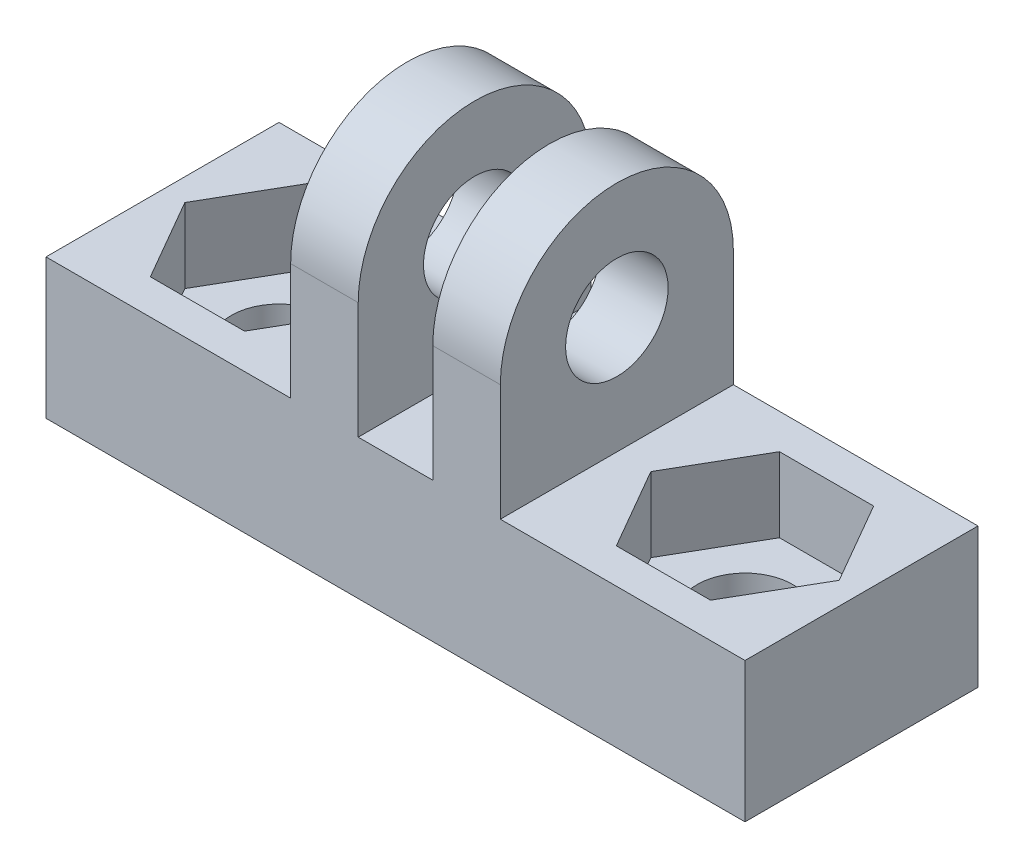
SolidWorks part; units mm, degrees
ref_plane "Front Plane" through (0, 0, 0) normal (0, 0, 1) x (1, 0, 0)
ref_plane "Top Plane" through (0, 0, 0) normal (0, 1, 0) x (1, 0, 0)
ref_plane "Right Plane" through (0, 0, 0) normal (1, 0, 0) x (0, 0, -1)
sketch "Sketch1" plane through (0, 0, 0) normal (0, 1, 0) x (1, 0, 0)
  line L1 (-5, -5) -> (5, -5)
  line L2 (-5, -5) -> (-5, 5)
  line L3 (-5, 5) -> (5, 5)
  line L4 (5, -5) -> (5, 5)
  line L5 (-5, -5) -> (5, 5) construction
  line L6 (-5, 5) -> (5, -5) construction
  circle A0 centre (0, 0) radius 2.05
  point P0 (0, 0)
  dimension "D3" = 4.1
  dimension "D1" = 10
  dimension "D2" = 10
extrude "Boss-Extrude1" add sketch "Sketch1" along normal blind 6
sketch "Sketch2" plane through (0, 6, 0) normal (0, 1, 0) x (1, 0, 0)
  line L1 (4.0415, 0) -> (2.0207, 3.5)
  line L2 (2.0207, 3.5) -> (-2.0207, 3.5)
  line L3 (-2.0207, 3.5) -> (-4.0415, 0)
  line L4 (-4.0415, 0) -> (-2.0207, -3.5)
  line L5 (-2.0207, -3.5) -> (2.0207, -3.5)
  line L6 (2.0207, -3.5) -> (4.0415, 0)
  circle A0 centre (0, 0) radius 3.5 construction
  dimension "D1" = 7
extrude "Cut-Extrude1" cut sketch "Sketch2" against normal blind 3.2
sketch "Sketch3" plane through (5, 0, 0) normal (1, 0, 0) x (0, 0, -1)
  line L0 (5, 6) -> (5, 0) construction
  line L1 (-5, 6) -> (5, 6)
  line L2 (-5, 6) -> (-5, 0)
  line L3 (-5, 0) -> (5, 0)
  line L4 (5, 6) -> (5, 0)
  line L5 (-5, 0) -> (5, 0) construction
extrude "Boss-Extrude2" add sketch "Sketch3" along normal blind 20
sketch "Sketch4" plane through (0, 6, 0) normal (0, 1, 0) x (1, 0, 0)
  circle A0 centre (20, 0) radius 2.05
  dimension "D2" = 4.1
  dimension "D1" = 20
extrude "Cut-Extrude2" cut sketch "Sketch4" against normal through all
sketch "Sketch5" plane through (0, 6, 0) normal (0, 1, 0) x (1, 0, 0)
  line L1 (24.0415, 0) -> (22.0207, 3.5)
  line L2 (22.0207, 3.5) -> (17.9793, 3.5)
  line L3 (17.9793, 3.5) -> (15.9585, 0)
  line L4 (15.9585, 0) -> (17.9793, -3.5)
  line L5 (17.9793, -3.5) -> (22.0207, -3.5)
  line L6 (22.0207, -3.5) -> (24.0415, 0)
  circle A0 centre (20, 0) radius 3.5 construction
  dimension "D1" = 7
extrude "Cut-Extrude3" cut sketch "Sketch5" against normal blind 3.2
ref_plane "Plane1" through (10, 0, 0) normal (-1, 0, 0) x (0, 0, 1)
sketch "Sketch6" plane through (10, 0, 0) normal (-1, 0, 0) x (0, 0, 1)
  line L0 (-5, 6) -> (5, 6) construction
  line L1 (5, 6) -> (5, 11)
  line L2 (-5, 6) -> (-5, 11)
  line L3 (5, 6) -> (-5, 6)
  circle A0 centre (0, 11) radius 2.2
  circle A1 centre (0, 11) radius 5 construction
  arc A2 (5, 11) -> (-5, 11) centre (0, 11) ccw
  dimension "D1" = 4.4
extrude "Boss-Extrude3" add sketch "Sketch6" along normal mid plane 9
sketch "Sketch7" plane through (10, 0, 0) normal (-1, 0, 0) x (0, 0, 1)
  line L1 (-5, 6) -> (5, 6)
  line L2 (-5, 6) -> (-5, 16.1147)
  line L3 (-5, 16.1147) -> (5, 16.1147)
  line L4 (5, 6) -> (5, 16.1147)
extrude "Cut-Extrude4" cut sketch "Sketch7" against normal mid plane 3.2
equation "\"A\"=1.7"
